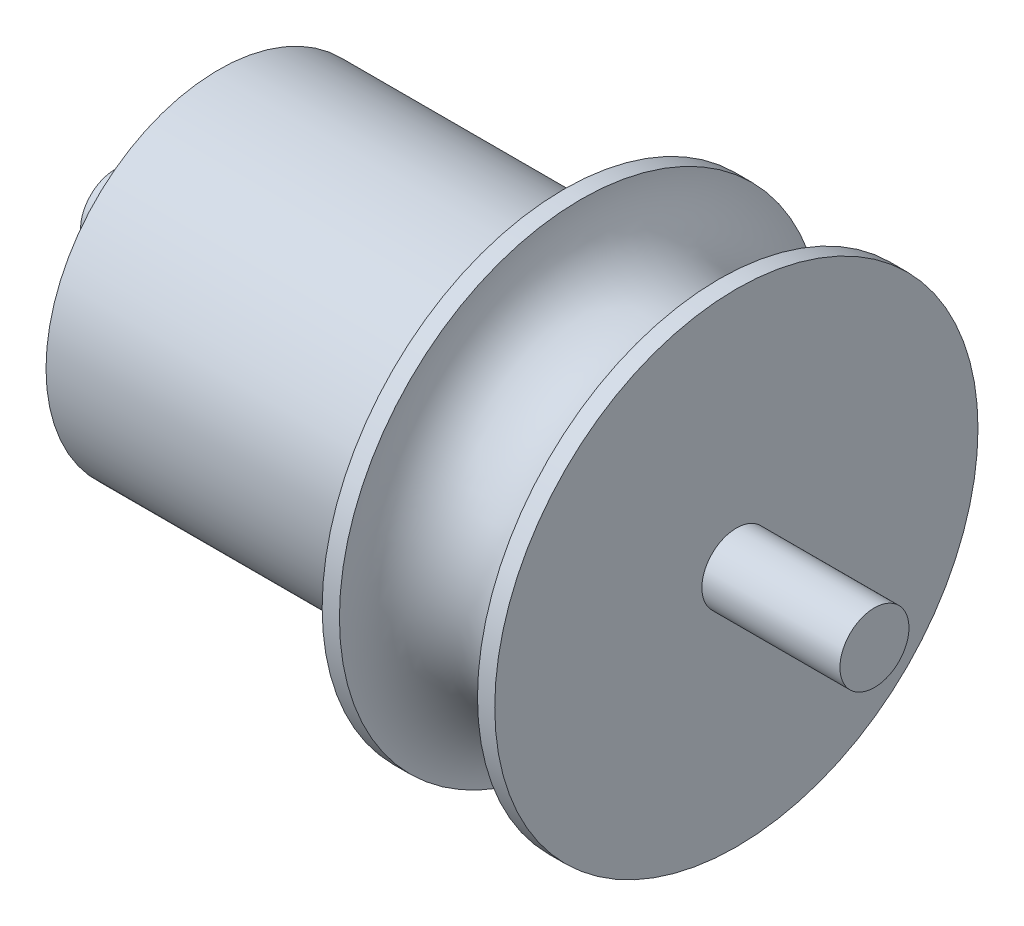
SolidWorks part; units mm, degrees
ref_plane "Front Plane" through (0, 0, 0) normal (0, 0, 1) x (1, 0, 0)
ref_plane "Top Plane" through (0, 0, 0) normal (0, 1, 0) x (1, 0, 0)
ref_plane "Right Plane" through (0, 0, 0) normal (1, 0, 0) x (0, 0, -1)
sketch "Sketch4" plane through (0, 0, 0) normal (0, 0, 1) x (1, 0, 0)
  line L0 (0, 0) -> (75, 0)
  line L1 (0, 0) -> (0, 25)
  line L2 (0, 25) -> (50, 25)
  line L3 (50, 25) -> (50, 35)
  line L8 (75, 35) -> (75, 0)
  line L12 (50, 35) -> (52.5, 35)
  line L14 (72.5, 35) -> (75, 35)
  arc A1 (52.5, 35) -> (72.5, 35) centre (62.5, 35) ccw
  dimension "D1" = 25
  dimension "D2" = 35
  dimension "D3" = 10
  dimension "D4" = 25
  dimension "D5" = 75
  dimension "D6" = 2.5
  dimension "D7" = 20
revolve "Revolve1" add sketch "Sketch4" angle 360 about L0
sketch "Sketch5" plane through (75, 0, 0) normal (1, 0, 0) x (0, 0, -1)
  circle A0 centre (0, 0) radius 5
extrude "Boss-Extrude3" add sketch "Sketch5" along normal blind 20 and the other way blind 90
